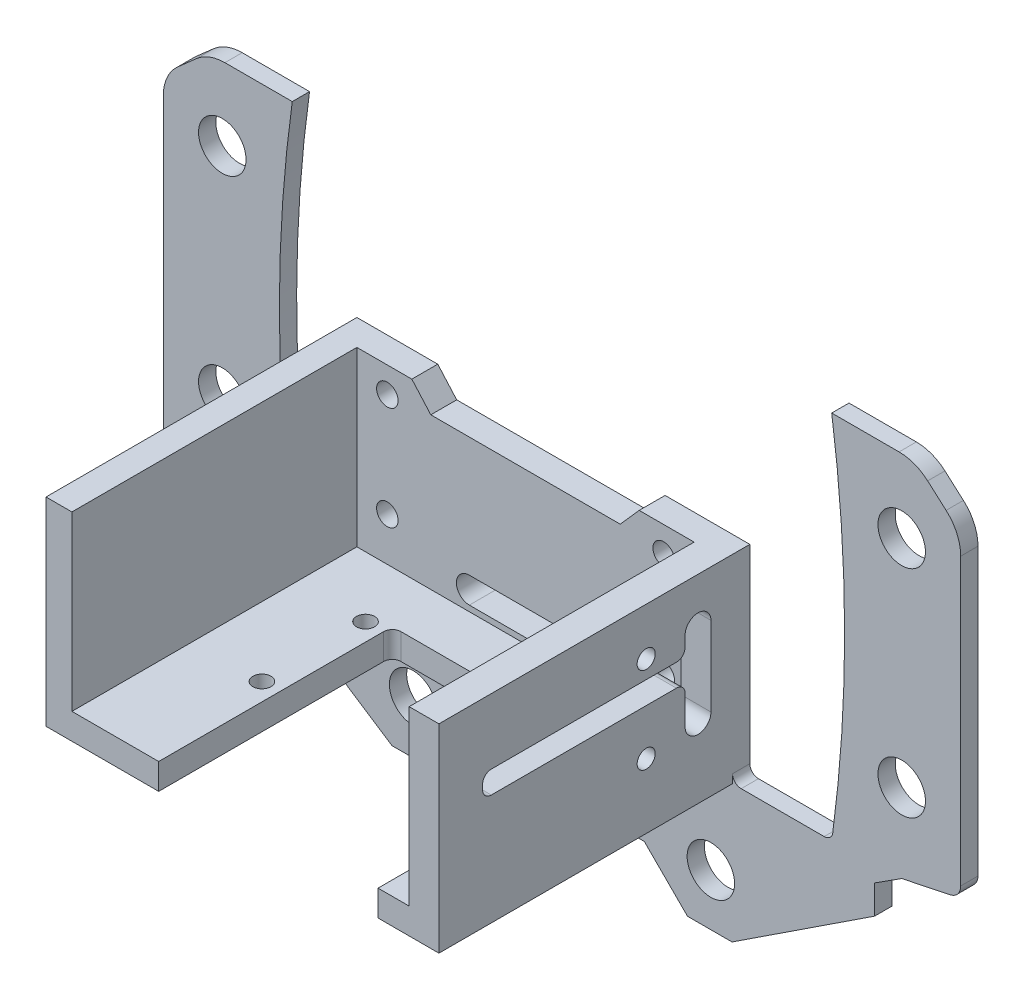
SolidWorks part; units mm, degrees
ref_plane "前视基准面" through (0, 0, 0) normal (0, 0, 1) x (1, 0, 0)
ref_plane "上视基准面" through (0, 0, 0) normal (0, 1, 0) x (1, 0, 0)
ref_plane "右视基准面" through (0, 0, 0) normal (1, 0, 0) x (0, 0, -1)
sketch "草图1" plane through (0, 0, 0) normal (0, 0, 1) x (1, 0, 0)
  line L346 (0, 0) -> (635.1265, 0) construction
  line L351 (-46.1708, 93.9243) -> (-46.1708, 145) construction
  line L411 (-31.2329, 137.5823) -> (-39.0335, 137.5823)
  line L414 (-42.3429, 136.3303) -> (-44.4803, 134.4431)
  line L445 (-46.1708, 130.695) -> (-46.1708, 97.6208)
  line L472 (42.3429, 136.3303) -> (44.4803, 134.4431)
  line L496 (31.2329, 137.5823) -> (39.0335, 137.5823)
  line L501 (-46.2756, 154.6927) -> (-33.8959, 144.8119) construction
  line L595 (-39.3354, 129.0823) -> (-39.3354, 104.0823) construction
  line L626 (-31.6538, 83.28) -> (-46.1708, 93.9243) construction
  line L641 (-9.5322, 83.7633) -> (9.5322, 83.7633)
  line L643 (-9.5322, 83.7633) -> (-14.5322, 78.7633)
  line L644 (30.4418, 78.7633) -> (14.5322, 78.7633) construction
  line L645 (9.5322, 83.7633) -> (14.5322, 78.7633)
  line L681 (-19.6882, 78.7633) -> (-14.5322, 78.7633)
  line L686 (14.5322, 78.7633) -> (19.6882, 78.7633)
  line L687 (-44.9631, 96.1323) -> (-39.3354, 94.9475)
  line L688 (-39.3354, 94.9475) -> (-36.2, 92.9426)
  line L691 (-36.2, 92.9426) -> (-36.2, 89.6081)
  line L692 (-36.2, 89.6081) -> (-19.6882, 78.7633)
  line L693 (36.2, 89.6081) -> (19.6882, 78.7633)
  line L694 (36.2, 92.9426) -> (36.2, 89.6081)
  line L695 (39.3354, 94.9475) -> (36.2, 92.9426)
  line L696 (44.9631, 96.1323) -> (39.3354, 94.9475)
  line L697 (46.1708, 130.695) -> (46.1708, 97.6208)
  line L699 (0, 134.5221) -> (0, 80.9968) construction
  line L700 (0, 0) -> (0, 155.4291) construction
  line L701 (-31.2329, 94.6706) -> (31.2329, 94.6706)
  circle A384 centre (39.3354, 129.0823) radius 2.75
  circle A385 centre (39.3354, 104.0823) radius 2.75
  circle A390 centre (17.238, 84.7633) radius 2.75
  circle A420 centre (-17.238, 84.7633) radius 2.75
  circle A421 centre (-39.3354, 104.0823) radius 2.75
  circle A422 centre (-39.3354, 129.0823) radius 2.75
  arc A457 (-32.8936, 142.3057) -> (-33.8959, 144.8119) centre (-35.6, 142.6768) ccw construction
  arc A473 (-44.4803, 134.4431) -> (-46.1708, 130.695) centre (-41.1708, 130.695) ccw
  arc A474 (-39.0335, 137.5823) -> (-42.3429, 136.3303) centre (-39.0335, 132.5823) ccw
  arc A475 (46.1708, 130.695) -> (44.4803, 134.4431) centre (41.1708, 130.695) ccw
  arc A476 (42.3429, 136.3303) -> (39.0335, 137.5823) centre (39.0335, 132.5823) ccw
  arc A490 (-46.1708, 97.6208) -> (-44.9631, 96.1323) centre (-44.6497, 97.6208) ccw
  arc A491 (46.1708, 97.6208) -> (44.9631, 96.1323) centre (44.6497, 97.6208) cw
  arc A493 (31.2329, 137.5823) -> (31.2329, 94.6706) centre (-122.1141, 116.1264) cw
  arc A494 (-31.2329, 137.5823) -> (-31.2329, 94.6706) centre (122.1141, 116.1264) ccw
  point P15 (0, 78.5133)
  point P26 (0, 90.339)
  point P46 (-46.1708, 132.9503)
  point P50 (-40.925, 137.5823)
  point P53 (46.1708, 132.9503)
  point P56 (40.925, 137.5823)
  point P90 (0, 90.339)
  dimension "D1" = 84.7633
  dimension "D5" = 44.319
  dimension "D6" = 19.319
  dimension "D7" = 22.0974
  dimension "D8" = 22.0974
  dimension "D15" = 33.5
  dimension "D17" = 6
  dimension "D38" = 5.5
  dimension "D27" = 135
  dimension "D10" = 138.556
  dimension "D13" = 93.9243
  dimension "D14" = 83.28
  dimension "D25" = 5
extrude "凸台-拉伸1" add sketch "草图1" along normal blind 2
sketch "草图2" plane through (0, 94.6706, 0) normal (0, 1, 0) x (1, 0, 0)
  line L0 (0, 11.5974) -> (0, -11.5974) construction
  line L1 (31.2329, 0) -> (-31.2329, 0) construction
  line L2 (12.3711, 0) -> (19.75, 0)
  line L3 (12.7, -8.95) -> (12.7, -36)
  line L4 (12.7, -36) -> (19.75, -36)
  line L5 (19.75, 0) -> (19.75, -36)
  line L6 (-12.7, -36) -> (-25.75, -36)
  line L7 (-25.75, 0) -> (-25.75, -36)
  line L8 (-12.3711, 0) -> (-25.75, 0)
  line L9 (-12.7, -8.95) -> (-12.7, -36)
  line L10 (-12.3711, 0) -> (12.3711, 0)
  line L11 (-12.7, -8.95) -> (12.7, -8.95)
  circle A0 centre (14.75, -10) radius 1.05
  circle A1 centre (-14.75, -10) radius 1.05
  circle A2 centre (-14.75, -22) radius 1.05
  circle A3 centre (14.75, -22) radius 1.05
  dimension "D1" = 2.1
  dimension "D4" = 12
  dimension "D2" = 29.5
  dimension "D3" = 2.05
  dimension "D5" = 11
  dimension "D6" = 5
  dimension "D7" = 26
  dimension "D8" = 10
extrude "云台背面" add sketch "草图2" along normal blind 3
sketch "草图3" plane through (0, 97.6706, 0) normal (0, 1, 0) x (1, 0, 0)
  line L0 (-25.75, -36) -> (-12.7, -36) construction
  line L1 (-25.75, 0) -> (-22.75, 0)
  line L2 (-25.75, 0) -> (-25.75, -36)
  line L3 (-25.75, -36) -> (-22.75, -36)
  line L4 (-22.75, 0) -> (-22.75, -36)
  line L5 (12.7, -36) -> (19.75, -36) construction
  line L6 (19.75, 0) -> (16.3, 0)
  line L7 (19.75, 0) -> (19.75, -36)
  line L8 (19.75, -36) -> (16.3, -36)
  line L9 (16.3, 0) -> (16.3, -36)
  circle A1 centre (14.75, -22) radius 1.05 construction
  dimension "D1" = 3
  dimension "D2" = 1.55
extrude "云台两侧" add sketch "草图3" along normal blind 20
sketch "草图5" plane through (16.3, 0, 0) normal (-1, 0, 0) x (0, 0, 1)
  line L0 (0, 97.6706) -> (36, 97.6706) construction
  line L1 (0, 117.6706) -> (0, 97.6706) construction
  line L2 (6, 112.2982) -> (6, 103.1077) construction
  line L3 (7.5, 112.2982) -> (7.5, 110.0967)
  line L4 (4.5, 112.2982) -> (4.5, 103.1077)
  line L5 (7.5, 107.5007) -> (7.5, 103.1077)
  line L6 (7.5, 110.0967) -> (30.9378, 110.0967)
  line L8 (7.5, 107.5007) -> (30.9378, 107.5007)
  line L9 (30.9378, 110.0967) -> (30.9378, 107.5007)
  circle A0 centre (12, 102.1706) radius 1.05
  circle A1 centre (12, 112.1706) radius 1.05
  arc A2 (7.5, 112.2982) -> (4.5, 112.2982) centre (6, 112.2982) ccw
  arc A3 (4.5, 103.1077) -> (7.5, 103.1077) centre (6, 103.1077) ccw
  point P6 (6, 107.703)
  point P19 (0, 0)
  point P20 (7.5, 105.4642)
  point P21 (7.5, 110.4995)
  point P22 (0, 0)
  point P23 (7.5, 110.0967)
  point P24 (7.5, 108.105)
  point P25 (7.5, 107.5007)
  dimension "D1" = 4.5
  dimension "D2" = 2.1
  dimension "D6" = 1.5
  dimension "D3" = 10
  dimension "D4" = 12
  dimension "D5" = 7.5
extrude "云台两侧过线及孔" cut sketch "草图5" against normal up to next
sketch "草图6" plane through (0, 0, 0) normal (0, 0, -1) x (-1, 0, 0)
  line L0 (-3.2803, 99.8367) -> (9.7303, 99.8367) construction
  line L1 (-16.3, 117.6706) -> (-9.9372, 117.6706)
  line L2 (-16.3, 117.6706) -> (-16.3, 97.6706)
  line L3 (-16.3, 97.6706) -> (22.75, 97.6706)
  line L4 (22.75, 117.6706) -> (22.75, 97.6706)
  line L5 (-3.2803, 101.3367) -> (9.7303, 101.3367)
  line L6 (-3.2803, 98.3367) -> (9.7303, 98.3367)
  line L7 (3.225, 126.4043) -> (3.225, 92.1512) construction
  line L8 (-9.9372, 117.6706) -> (-7.7418, 115.1898)
  line L9 (-7.7418, 115.1898) -> (14.1918, 115.1898)
  line L10 (16.3872, 117.6706) -> (14.1918, 115.1898)
  line L11 (16.3872, 117.6706) -> (22.75, 117.6706)
  arc A0 (-3.2803, 101.3367) -> (-3.2803, 98.3367) centre (-3.2803, 99.8367) ccw
  arc A1 (9.7303, 98.3367) -> (9.7303, 101.3367) centre (9.7303, 99.8367) ccw
  circle A2 centre (-12.775, 114.6983) radius 1.2456
  circle A3 centre (19.225, 114.6983) radius 1.2456
  circle A4 centre (-12.775, 102.6983) radius 1.2456
  circle A5 centre (19.225, 102.6983) radius 1.2456
  point P8 (3.225, 99.8367)
  point P16 (3.225, 97.6706)
  point P28 (3.225, 115.1898)
  point P29 (-9.9372, 117.6706)
  dimension "D1" = 1.5
  dimension "D2" = 32
  dimension "D3" = 12
extrude "云台上面" add sketch "草图6" against normal blind 3
fillet "圆角1" radius 1 10 edges at (12.7, 96.1706, 8.95) (-12.7, 96.1706, 8.95) (31.2329, 94.6706, 1) (19.75, 94.6706, 1) (-25.75, 94.6706, 1) (-31.2329, 94.6706, 1) (18.025, 110.0967, 7.5) (18.025, 107.5007, 7.5) (18.025, 107.5007, 30.9378) (18.025, 110.0967, 30.9378)
